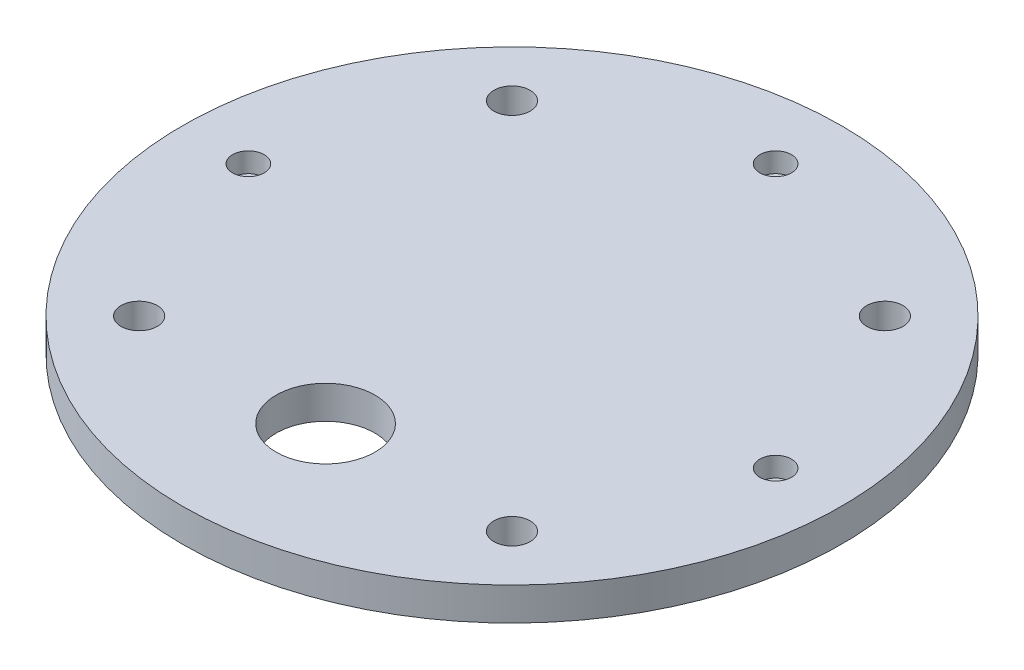
SolidWorks part; units mm, degrees
ref_plane "前视基准面" through (0, 0, 0) normal (0, 0, 1) x (1, 0, 0)
ref_plane "上视基准面" through (0, 0, 0) normal (0, 1, 0) x (1, 0, 0)
ref_plane "右视基准面" through (0, 0, 0) normal (1, 0, 0) x (0, 0, -1)
sketch "草图1" plane through (0, 0, 0) normal (0, 1, 0) x (1, 0, 0)
  circle A0 centre (0, 0) radius 50
  dimension "D1" = 100
extrude "凸台-拉伸1" add sketch "草图1" against normal blind 5
sketch "草图5" plane through (0, 0, 0) normal (0, 1, 0) x (1, 0, 0)
  circle A0 centre (28.2843, 28.2843) radius 2.75
  circle A1 centre (28.2843, -28.2843) radius 2.75
  circle A2 centre (-28.2843, -28.2843) radius 2.75
  circle A3 centre (-28.2843, 28.2843) radius 2.75
  point P12 (0, 0)
  dimension "D1" = 5.5
  dimension "D2" = 4
extrude "切除-拉伸4" cut sketch "草图5" against normal blind 24
sketch "草图6" plane through (0, 0, 0) normal (0, 1, 0) x (1, 0, 0)
  line L0 (-28.2843, -28.2843) -> (28.2843, -28.2843) construction
  circle A0 centre (0, -28.2843) radius 7.5
  dimension "D1" = 15
extrude "切除-拉伸5" cut sketch "草图6" against normal blind 24
sketch "草图7" plane through (0, 0, 0) normal (0, 1, 0) x (1, 0, 0)
  circle A0 centre (40, 0) radius 2.4
  circle A1 centre (0, 40) radius 2.4
  circle A2 centre (-40, 0) radius 2.4
  dimension "D1" = 4.8
  dimension "D2" = 40
  dimension "D3" = 4.8
  dimension "D4" = 40
  dimension "D5" = 4.8
  dimension "D6" = 40
extrude "切除-拉伸6" cut sketch "草图7" against normal blind 3
